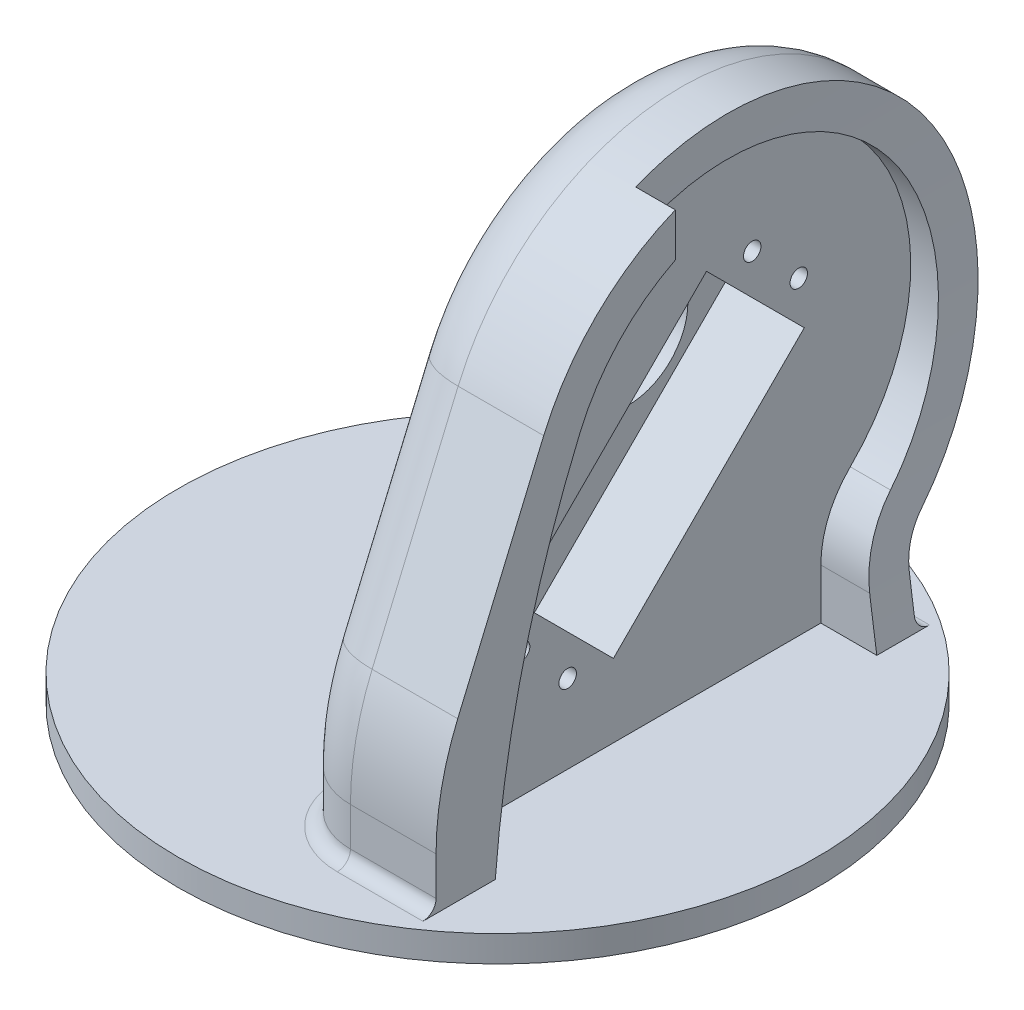
SolidWorks part; units mm, degrees
ref_plane "Front Plane" through (0, 0, 0) normal (0, 0, 1) x (1, 0, 0)
ref_plane "Top Plane" through (0, 0, 0) normal (0, 1, 0) x (1, 0, 0)
ref_plane "Right Plane" through (0, 0, 0) normal (1, 0, 0) x (0, 0, -1)
sketch "Sketch2" plane through (0, 0, 0) normal (0, 1, 0) x (1, 0, 0)
  circle A0 centre (0, 0) radius 48.5
  circle A1 centre (0, 7.25) radius 1.5
  circle A2 centre (0, -7.25) radius 1.5
  point P7 (0, 0)
  point P8 (0, 0)
  dimension "D1" = 97
  dimension "D4" = 3
  dimension "D5" = 3
  dimension "D2" = 14.5
  dimension "D3" = 7.25
extrude "Boss-Extrude1" add sketch "Sketch2" against normal blind 4
sketch "Sketch3" plane through (0, -4, 0) normal (0, -1, 0) x (-1, 0, 0)
  circle A0 centre (0, 0) radius 3.75
  dimension "D1" = 7.5
extrude "Cut-Extrude1" cut sketch "Sketch3" against normal blind 1.5
sketch "Sketch4" plane through (0, 0, 0) normal (1, 0, 0) x (0, 0, -1)
  line L4 (-14.4702, 52.3514) -> (-27.5292, 21.6494)
  line L8 (-30.34, 7.86) -> (-30.34, 0)
  line L9 (48.5, 0) -> (-48.5, 0) construction
  line L10 (-30.34, 0) -> (31.0971, 0)
  line L11 (31.0971, 0) -> (31.0971, 7.64)
  arc A0 (-27.5292, 21.6494) -> (-30.34, 7.86) centre (4.89, 7.86) ccw
  arc A2 (31.0971, 7.64) -> (35.5648, 18.3204) centre (46.0971, 7.64) cw
  arc A3 (35.5648, 18.3204) -> (-14.4702, 52.3514) centre (13.91, 40.28) ccw
  circle A4 centre (13.91, 40.28) radius 9
  dimension "D3" = 35.23
  dimension "D4" = 15
  dimension "D5" = 18
  dimension "D1" = 7.86
  dimension "D2" = 7.64
  dimension "D6" = 13.91
  dimension "D7" = 40.28
extrude "Boss-Extrude2" add sketch "Sketch4" along normal blind 14 from offset 4
sketch "Sketch6" plane through (0, 0, 0) normal (1, 0, 0) x (0, 0, -1)
  line L0 (-0.41, 11.11) -> (-15.2592, 25.9592)
  line L1 (-0.41, 11.11) -> (28.5814, 40.1014)
  line L2 (-15.2592, 25.9592) -> (13.7321, 54.9506)
  line L3 (28.5814, 40.1014) -> (13.7321, 54.9506)
  line L4 (-30.34, 0) -> (31.0971, 0) construction
  line L5 (48.5, 0) -> (-48.5, 0) construction
  line L6 (-0.7636, 40.4549) -> (14.0857, 25.6057) construction
  line L7 (6.6611, 33.0303) -> (26.6233, 52.9925) construction
  line L8 (20.6743, 54.1146) -> (27.7453, 47.0435) construction
  circle A0 centre (20.6743, 54.1146) radius 1.325
  circle A1 centre (27.7453, 47.0435) radius 1.325
  circle A2 centre (-7.3521, 11.946) radius 1.325
  circle A3 centre (-14.4232, 19.0171) radius 1.325
  dimension "D6" = 2.65
  dimension "D7" = 2.65
  dimension "D1" = 0.41
  dimension "D2" = 11.11
  dimension "D3" = 45
  dimension "D4" = 41
  dimension "D5" = 21
  dimension "D9" = 5
extrude "Cut-Extrude2" cut sketch "Sketch6" along normal through all from offset 6
sketch "Sketch8" plane through (18, 0, 0) normal (1, 0, 0) x (0, 0, -1)
  line L0 (34.0971, 0) -> (34.0971, 7.64) construction
  line L1 (-17.2308, 53.5257) -> (-30.2898, 22.8237) construction
  line L2 (-33.34, 7.86) -> (-33.34, 0) construction
  line L3 (37.0971, 0) -> (37.0971, 7.64)
  line L4 (31.0971, 0) -> (31.0971, 7.64)
  line L5 (-14.4702, 52.3514) -> (-27.5292, 21.6494)
  line L6 (-30.34, 7.86) -> (-30.34, 0)
  line L7 (-30.34, 0) -> (31.0971, 0)
  line L8 (31.0971, 0) -> (31.0971, 7.64)
  line L12 (-19.9914, 54.6999) -> (-33.0505, 23.9979)
  line L13 (-36.34, 7.86) -> (-36.34, 0)
  line L14 (-30.34, 0) -> (31.0971, 0) construction
  line L15 (-14.4702, 52.3514) -> (-27.5292, 21.6494) construction
  line L16 (-30.34, 7.86) -> (-30.34, 0) construction
  line L17 (-36.34, 0) -> (-27.34, 0)
  line L18 (31.0971, 0) -> (37.0971, 0)
  line L21 (-14.4702, 52.3514) -> (-27.5292, 21.6494) construction
  arc A0 (37.6713, 16.1844) -> (34.0971, 7.64) centre (46.0971, 7.64) ccw construction
  arc A1 (37.6713, 16.1844) -> (-17.2308, 53.5257) centre (13.91, 40.28) ccw construction
  arc A2 (-30.2898, 22.8237) -> (-33.34, 7.86) centre (4.89, 7.86) ccw construction
  arc A3 (35.5648, 18.3204) -> (31.0971, 7.64) centre (46.0971, 7.64) ccw
  arc A4 (35.5648, 18.3204) -> (-14.4702, 52.3514) centre (13.91, 40.28) ccw
  arc A5 (-27.5292, 21.6494) -> (-30.34, 7.86) centre (4.89, 7.86) ccw
  arc A6 (35.5648, 18.3204) -> (31.0971, 7.64) centre (46.0971, 7.64) ccw
  arc A7 (35.5648, 18.3204) -> (-14.4702, 52.3514) centre (13.91, 40.28) ccw
  arc A9 (39.7777, 14.0483) -> (37.0971, 7.64) centre (46.0971, 7.64) ccw
  arc A10 (39.7777, 14.0483) -> (-19.9914, 54.6999) centre (13.91, 40.28) ccw
  arc A11 (-33.0505, 23.9979) -> (-36.34, 7.86) centre (4.89, 7.86) ccw
  arc A12 (-14.4702, 52.3514) -> (-27.34, 0) centre (140.1577, -13.4192) ccw
  arc A13 (-27.5292, 21.6494) -> (-30.34, 7.86) centre (4.89, 7.86) ccw construction
  dimension "D4" = 3
  dimension "D1" = 0
  dimension "D2" = 3
  dimension "D3" = 3
extrude "Boss-Extrude3" add sketch "Sketch8" along normal blind 9 and the other way up to surface other way up to face at (4, 19.8367, -2.0028)
sketch "Sketch9" plane through (0, 0, 0) normal (0, 0, 1) x (1, 0, 0)
  line L0 (27, 77.1208) -> (21, 77.1208)
  line L1 (27, 77.1208) -> (4, 77.1208) construction
  line L2 (48.5, 0) -> (-48.5, 0) construction
  line L3 (27, 7.86) -> (27, 0) construction
  line L4 (26.5, 0) -> (27, 0)
  line L5 (27, 77.1208) -> (27, 0)
  arc A0 (21, 77.1208) -> (26.5, 0) centre (520.9904, 74.0219) ccw
  dimension "D1" = 500
  dimension "D2" = 0.5
  dimension "D3" = 6
extrude "Cut-Extrude3" cut sketch "Sketch9" against normal through all
fillet "Fillet1" radius 10 6 edges at (4, 3.82, -37.0971) (4, 11.1132, -37.7942) (4, 3.93, 36.34) (4, 16.0949, 35.5093) (4, 39.3489, 26.521) (4, 70.7426, -34.6289)
fillet "Fillet2" radius 2 5 edges at (20.5, 0, 36.34) (6.9289, 0, 33.4111) (20.25, 0, -37.0971) (6.9289, 0, -34.1681) (4, 0, -0.3785)
